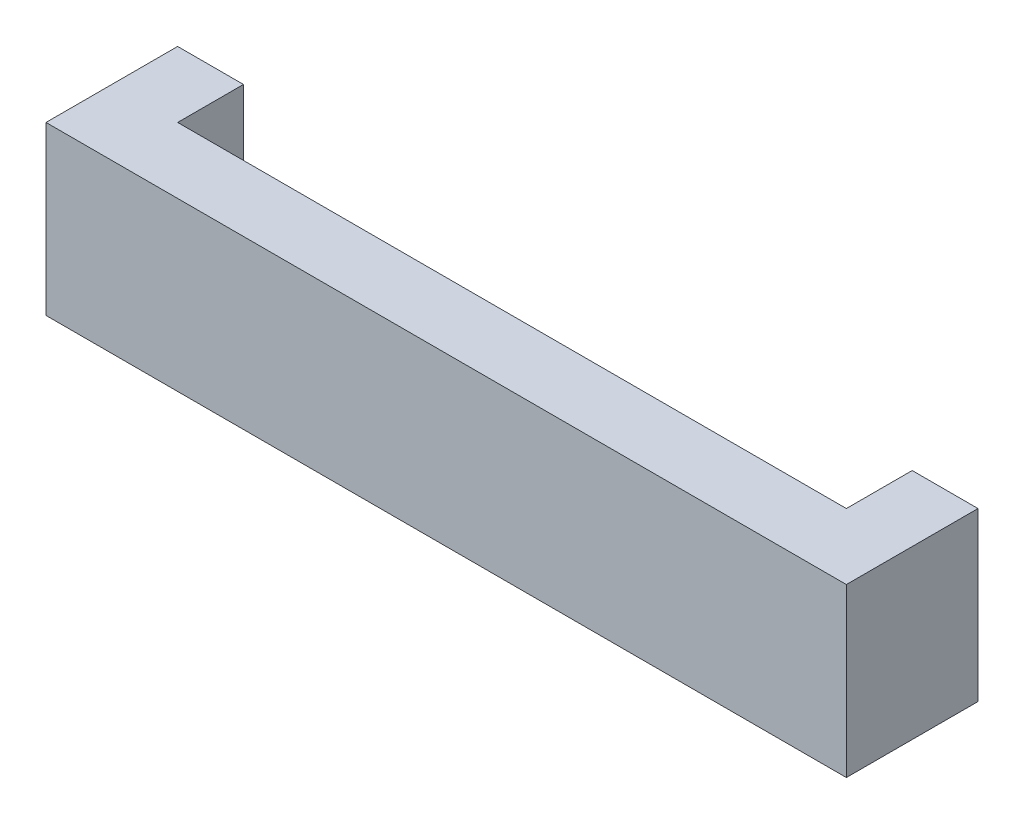
SolidWorks part; units mm, degrees
ref_plane "Front Plane" through (0, 0, 0) normal (0, 0, 1) x (1, 0, 0)
ref_plane "Top Plane" through (0, 0, 0) normal (0, 1, 0) x (1, 0, 0)
ref_plane "Right Plane" through (0, 0, 0) normal (1, 0, 0) x (0, 0, -1)
sketch "Sketch1" plane through (0, 0, 0) normal (0, 1, 0) x (1, 0, 0)
  line L0 (-30.4, 5) -> (-25.4, 5)
  line L1 (-25.4, 5) -> (-25.4, 0)
  line L2 (-25.4, 0) -> (25.4, 0)
  line L3 (25.4, 0) -> (25.4, 5)
  line L4 (25.4, 5) -> (30.4, 5)
  line L5 (30.4, 5) -> (30.4, -5)
  line L6 (30.4, -5) -> (-30.4, -5)
  line L7 (-30.4, -5) -> (-30.4, 5)
  line L8 (-25.4, 0) -> (-25.4, -5) construction
  point P8 (0, -5)
  point P11 (-30.4, 0)
  point P12 (19.05, -1.0278)
  dimension "D1" = 50.8
  dimension "D2" = 5
  dimension "D3" = 5
extrude "Boss-Extrude1" add sketch "Sketch1" along normal mid plane 12.7
